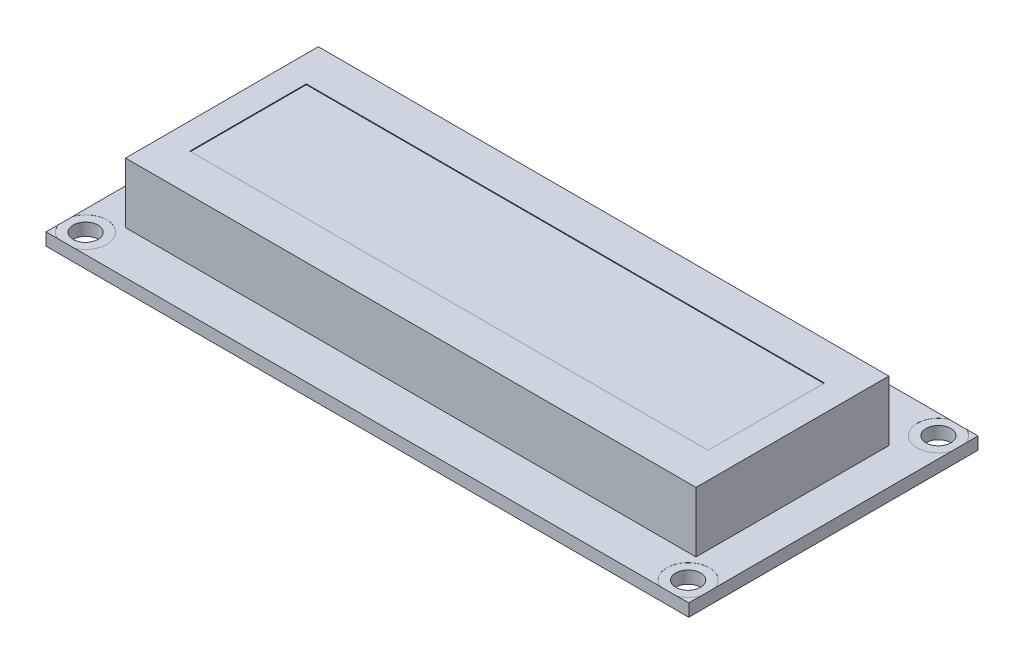
SolidWorks part; units mm, degrees
ref_plane "Front Plane" through (0, 0, 0) normal (0, 0, 1) x (1, 0, 0)
ref_plane "Top Plane" through (0, 0, 0) normal (0, 1, 0) x (1, 0, 0)
ref_plane "Right Plane" through (0, 0, 0) normal (1, 0, 0) x (0, 0, -1)
sketch "Sketch1" plane through (0, 0, 0) normal (0, 1, 0) x (1, 0, 0)
  line L1 (-40, -18) -> (40, -18)
  line L2 (-40, -18) -> (-40, 18)
  line L3 (-40, 18) -> (40, 18)
  line L4 (40, -18) -> (40, 18)
  line L5 (-40, -18) -> (40, 18) construction
  line L6 (-40, 18) -> (40, -18) construction
  point P0 (0, 0)
  dimension "D1" = 36
  dimension "D2" = 80
extrude "PCB" add sketch "Sketch1" along normal blind 1.55
sketch "Sketch2" plane through (0, 1.55, 0) normal (0, 1, 0) x (1, 0, 0)
  line L0 (-42.4796, 0) -> (42.3992, 0) construction
  line L1 (-37.5, 15.575) -> (37.5, 15.575) construction
  circle A0 centre (-37.5, 15.575) radius 1.55
  circle A1 centre (37.5, 15.575) radius 1.55
  circle A2 centre (37.5, -15.575) radius 1.55
  circle A3 centre (-37.5, -15.575) radius 1.55
  circle A4 centre (-37.5, 15.575) radius 2.6 construction
  point P12 (0, 15.575)
  dimension "D1" = 3.1
  dimension "D4" = 5.2
  dimension "D2" = 75
  dimension "D3" = 15.575
extrude "MountingHoles" cut sketch "Sketch2" against normal through all
sketch "Sketch3" plane through (0, 1.55, 0) normal (0, 1, 0) x (1, 0, 0)
  line L0 (0, -21.8483) -> (0, 21.8483) construction
  line L1 (-44.6988, 0) -> (43.4961, 0) construction
  line L2 (40, 18) -> (-40, 18) construction
  line L3 (-32.9, 18) -> (-31.1, 18)
  line L4 (-32.9, 18) -> (-32.9, 16)
  line L5 (-30.36, 18) -> (-30.36, 16)
  line L6 (-31.1, 18) -> (-31.1, 16)
  line L7 (-30.36, 18) -> (-28.56, 18)
  line L8 (-28.56, 18) -> (-28.56, 16)
  line L9 (-27.82, 18) -> (-27.82, 16)
  line L10 (-27.82, 18) -> (-26.02, 18)
  line L11 (-26.02, 18) -> (-26.02, 16)
  line L12 (-25.28, 18) -> (-25.28, 16)
  line L13 (-25.28, 18) -> (-23.48, 18)
  line L14 (-23.48, 18) -> (-23.48, 16)
  line L15 (-22.74, 18) -> (-22.74, 16)
  line L16 (-22.74, 18) -> (-20.94, 18)
  line L17 (-20.94, 18) -> (-20.94, 16)
  line L18 (-20.2, 18) -> (-20.2, 16)
  line L19 (-20.2, 18) -> (-18.4, 18)
  line L20 (-18.4, 18) -> (-18.4, 16)
  line L21 (-17.66, 18) -> (-17.66, 16)
  line L22 (-17.66, 18) -> (-15.86, 18)
  line L23 (-15.86, 18) -> (-15.86, 16)
  line L24 (-15.12, 18) -> (-15.12, 16)
  line L25 (-15.12, 18) -> (-13.32, 18)
  line L26 (-13.32, 18) -> (-13.32, 16)
  line L27 (-12.58, 18) -> (-12.58, 16)
  line L28 (-12.58, 18) -> (-10.78, 18)
  line L29 (-10.78, 18) -> (-10.78, 16)
  line L30 (-10.04, 18) -> (-10.04, 16)
  line L31 (-10.04, 18) -> (-8.24, 18)
  line L32 (-8.24, 18) -> (-8.24, 16)
  line L33 (-7.5, 18) -> (-7.5, 16)
  line L34 (-7.5, 18) -> (-5.7, 18)
  line L35 (-5.7, 18) -> (-5.7, 16)
  line L36 (-4.96, 18) -> (-4.96, 16)
  line L37 (-4.96, 18) -> (-3.16, 18)
  line L38 (-3.16, 18) -> (-3.16, 16)
  line L39 (-2.42, 18) -> (-2.42, 16)
  line L40 (-2.42, 18) -> (-0.62, 18)
  line L41 (-0.62, 18) -> (-0.62, 16)
  line L42 (0.12, 18) -> (0.12, 16)
  line L43 (0.12, 18) -> (1.92, 18)
  line L44 (1.92, 18) -> (1.92, 16)
  line L45 (2.66, 18) -> (2.66, 16)
  line L46 (2.66, 18) -> (4.46, 18)
  line L47 (4.46, 18) -> (4.46, 16)
  line L48 (5.2, 18) -> (5.2, 16)
  line L49 (5.2, 18) -> (7, 18)
  line L50 (7, 18) -> (7, 16)
  circle A0 centre (-37.5, 15.575) radius 2.65
  circle A1 centre (37.5, 15.575) radius 2.65
  circle A2 centre (37.5, -15.575) radius 2.65
  circle A3 centre (-37.5, -15.575) radius 2.65
  arc A4 (-32.9, 16) -> (-31.1, 16) centre (-32, 16) ccw
  arc A5 (-30.36, 16) -> (-28.56, 16) centre (-29.46, 16) ccw
  arc A6 (-27.82, 16) -> (-26.02, 16) centre (-26.92, 16) ccw
  arc A7 (-25.28, 16) -> (-23.48, 16) centre (-24.38, 16) ccw
  arc A8 (-22.74, 16) -> (-20.94, 16) centre (-21.84, 16) ccw
  arc A9 (-20.2, 16) -> (-18.4, 16) centre (-19.3, 16) ccw
  arc A10 (-17.66, 16) -> (-15.86, 16) centre (-16.76, 16) ccw
  arc A11 (-15.12, 16) -> (-13.32, 16) centre (-14.22, 16) ccw
  arc A12 (-12.58, 16) -> (-10.78, 16) centre (-11.68, 16) ccw
  arc A13 (-10.04, 16) -> (-8.24, 16) centre (-9.14, 16) ccw
  arc A14 (-7.5, 16) -> (-5.7, 16) centre (-6.6, 16) ccw
  arc A15 (-4.96, 16) -> (-3.16, 16) centre (-4.06, 16) ccw
  arc A16 (-2.42, 16) -> (-0.62, 16) centre (-1.52, 16) ccw
  arc A17 (0.12, 16) -> (1.92, 16) centre (1.02, 16) ccw
  arc A18 (2.66, 16) -> (4.46, 16) centre (3.56, 16) ccw
  arc A19 (5.2, 16) -> (7, 16) centre (6.1, 16) ccw
  point P21 (0, 0)
  dimension "D1" = 5.3
  dimension "D2" = 1.8
  dimension "D3" = 5.5
  dimension "D4" = 2
  dimension "D6" = 2.54
  dimension "D5" = 16
extrude "Pads" cut sketch "Sketch3" against normal blind 0.01
sketch "Sketch4" plane through (0, 1.55, 0) normal (0, 1, 0) x (1, 0, 0)
  circle A0 centre (-32, 16) radius 0.5
  circle A1 centre (-29.46, 16) radius 0.5
  circle A2 centre (-26.92, 16) radius 0.5
  circle A3 centre (-24.38, 16) radius 0.5
  circle A4 centre (-21.84, 16) radius 0.5
  circle A5 centre (-19.3, 16) radius 0.5
  circle A6 centre (-16.76, 16) radius 0.5
  circle A7 centre (-14.22, 16) radius 0.5
  circle A8 centre (-11.68, 16) radius 0.5
  circle A9 centre (-9.14, 16) radius 0.5
  circle A10 centre (-6.6, 16) radius 0.5
  circle A11 centre (-4.06, 16) radius 0.5
  circle A12 centre (-1.52, 16) radius 0.5
  circle A13 centre (1.02, 16) radius 0.5
  circle A14 centre (3.56, 16) radius 0.5
  circle A15 centre (6.1, 16) radius 0.5
  dimension "D1" = 1
  dimension "D2" = 16
extrude "ConnecterHoles" cut sketch "Sketch4" against normal through all
sketch "Sketch5" plane through (0, 1.55, 0) normal (0, 1, 0) x (1, 0, 0)
  line L0 (36.4314, 18) -> (7, 18) construction
  line L1 (-35.5, -12.6) -> (35.5, -12.6)
  line L2 (-35.5, -12.6) -> (-35.5, 11.4)
  line L3 (-35.5, 11.4) -> (35.5, 11.4)
  line L4 (35.5, -12.6) -> (35.5, 11.4)
  line L5 (-35.5, -12.6) -> (35.5, 11.4) construction
  line L6 (-35.5, 11.4) -> (35.5, -12.6) construction
  point P0 (0, -0.6)
  dimension "D1" = 24
  dimension "D2" = 71
  dimension "D3" = 6.6
extrude "PanelBody" add sketch "Sketch5" along normal blind 7.5
sketch "Sketch6" plane through (0, 9.05, 0) normal (0, 1, 0) x (1, 0, 0)
  line L0 (35.5, -0.6) -> (-35.5, -0.6) construction
  line L1 (-32.25, -7.85) -> (32.25, -7.85)
  line L2 (-32.25, -7.85) -> (-32.25, 6.65)
  line L3 (-32.25, 6.65) -> (32.25, 6.65)
  line L4 (32.25, -7.85) -> (32.25, 6.65)
  line L5 (-32.25, -7.85) -> (32.25, 6.65) construction
  line L6 (-32.25, 6.65) -> (32.25, -7.85) construction
  line L7 (35.5, -12.6) -> (35.5, 11.4) construction
  line L8 (-35.5, 11.4) -> (-35.5, -12.6) construction
  point P0 (0, -0.6)
  dimension "D1" = 14.5
  dimension "D2" = 64.5
extrude "Screen" cut sketch "Sketch6" against normal blind 0.1
